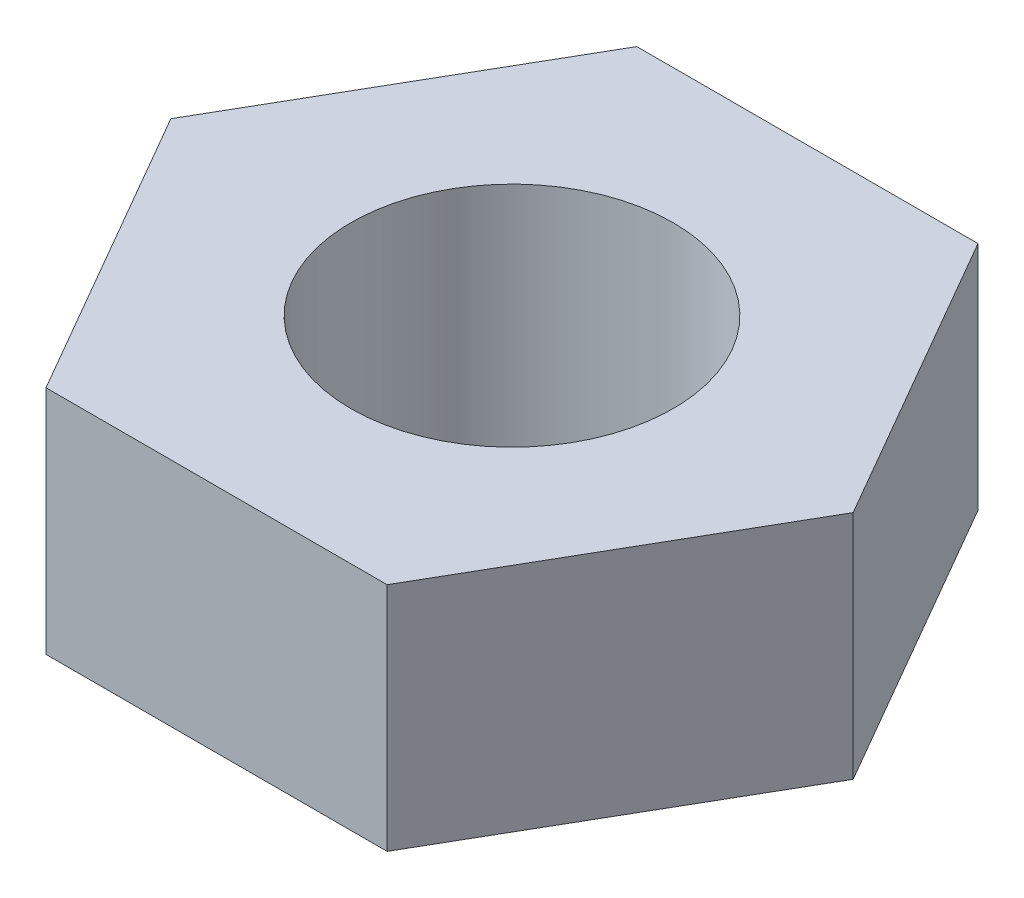
SolidWorks part; units mm, degrees
material "铸造不锈钢"
ref_plane "前视基准面" through (0, 0, 0) normal (0, 0, 1) x (1, 0, 0)
ref_plane "上视基准面" through (0, 0, 0) normal (0, 1, 0) x (1, 0, 0)
ref_plane "右视基准面" through (0, 0, 0) normal (1, 0, 0) x (0, 0, -1)
other "Configuration Table"
sketch "草图1" plane through (0, 0, 0) normal (0, 1, 0) x (1, 0, 0)
  line L1 (3.1754, 0) -> (1.5877, 2.75)
  line L2 (1.5877, 2.75) -> (-1.5877, 2.75)
  line L3 (-1.5877, 2.75) -> (-3.1754, 0)
  line L4 (-3.1754, 0) -> (-1.5877, -2.75)
  line L5 (-1.5877, -2.75) -> (1.5877, -2.75)
  line L6 (1.5877, -2.75) -> (3.1754, 0)
  circle A0 centre (0, 0) radius 2.75 construction
  dimension "D1" = 5.5
extrude "凸台-拉伸1" add sketch "草图1" along normal blind 2.15
sketch "草图3" plane through (0, 0, 0) normal (0, 1, 0) x (1, 0, 0)
  circle A0 centre (0, 0) radius 1.5
extrude "切除-拉伸1" cut sketch "草图3" against normal blind 0.8 and the other way blind 3
